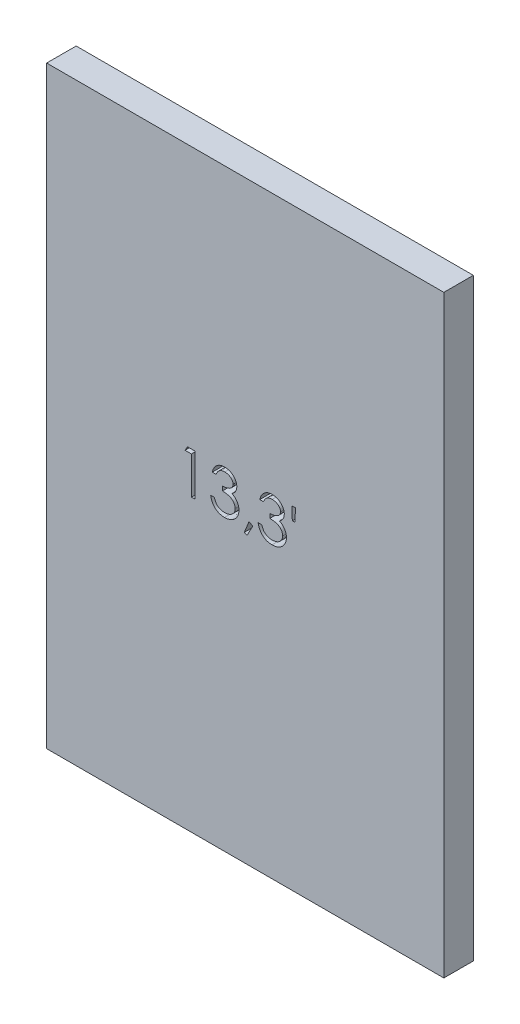
SolidWorks part; units mm, degrees
ref_plane "Plano frontal" through (0, 0, 0) normal (0, 0, 1) x (1, 0, 0)
ref_plane "Plano superior" through (0, 0, 0) normal (0, 1, 0) x (1, 0, 0)
ref_plane "Plano direito" through (0, 0, 0) normal (1, 0, 0) x (0, 0, -1)
sketch "Esboço1" plane through (0, 0, 0) normal (0, 0, 1) x (1, 0, 0)
  line L1 (101, -151) -> (-101, -151)
  line L2 (101, -151) -> (101, 151)
  line L3 (101, 151) -> (-101, 151)
  line L4 (-101, -151) -> (-101, 151)
  line L5 (101, -151) -> (-101, 151) construction
  line L6 (101, 151) -> (-101, -151) construction
  point P0 (0, 0)
  dimension "D1" = 302
  dimension "D2" = 202
extrude "Ressalto-extrusão1" add sketch "Esboço1" along normal blind 15
sketch "Esboço3" plane through (0, 0, 15) normal (0, 0, 1) x (1, 0, 0)
  text T0 "13,3'\r\n" font "Century Gothic" height in points 80
extrude "Corte-extrusão1" cut sketch "Esboço3" against normal blind 10
